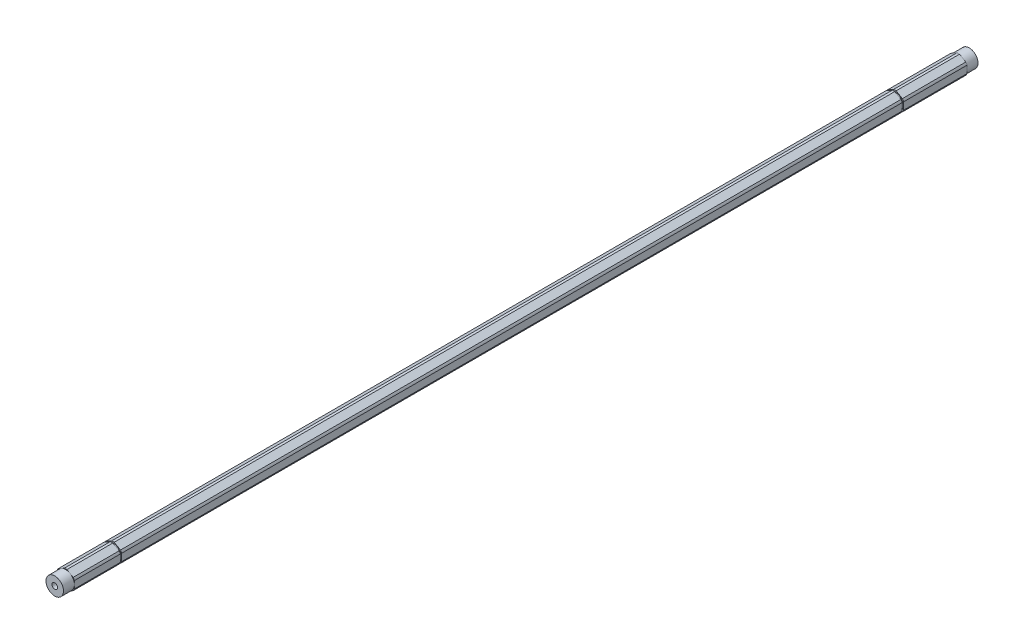
SolidWorks part; units mm, degrees
material "7075-T6 (SN)"
ref_plane "Front Plane" through (0, 0, 0) normal (0, 0, 1) x (1, 0, 0)
ref_plane "Top Plane" through (0, 0, 0) normal (0, 1, 0) x (1, 0, 0)
ref_plane "Right Plane" through (0, 0, 0) normal (1, 0, 0) x (0, 0, -1)
sketch "Sketch1" plane through (0, 0, 0) normal (0, 0, 1) x (1, 0, 0)
  line L1 (0, 7.3323) -> (-6.35, 3.6662)
  line L2 (-6.35, 3.6662) -> (-6.35, -3.6662)
  line L3 (-6.35, -3.6662) -> (0, -7.3323)
  line L4 (0, -7.3323) -> (6.35, -3.6662)
  line L5 (6.35, -3.6662) -> (6.35, 3.6662)
  line L6 (6.35, 3.6662) -> (0, 7.3323)
  circle A0 centre (0, 0) radius 6.35 construction
  circle A1 centre (0, 0) radius 2.0193
  circle A2 centre (0, 0) radius 6.875
  dimension "D1" = 12.7
  dimension "D2" = 4.0386
  dimension "D3" = 13.75
extrude "Boss-Extrude1" add sketch "Sketch1" along normal mid plane 663.575 contours L5 A2 L6 L1 L2 L3 L4 A1
sketch "Sketch2" plane through (0, 0, -331.7875) normal (0, 0, -1) x (-1, 0, 0)
  circle A0 centre (0, 0) radius 6.35
  dimension "D1" = 12.7
extrude "Cut-Extrude-Thin1" cut sketch "Sketch2" against normal blind 7.9375 thin
sketch "Sketch3" plane through (0, 0, 0) normal (0, 1, 0) x (1, 0, 0)
  line L0 (8.1546, -289.5219) -> (5.9436, -289.5219)
  line L1 (8.6172, 277.8125) -> (5.9436, 277.8125)
  line L2 (8.6172, 277.8125) -> (8.6172, 276.8219)
  line L3 (8.6172, 276.8219) -> (5.9436, 276.8219)
  line L4 (5.9436, 277.8125) -> (5.9436, 276.8219)
  line L5 (8.1546, -289.5219) -> (8.1546, -290.5125)
  line L6 (8.1546, -290.5125) -> (5.9436, -290.5125)
  line L7 (5.9436, -289.5219) -> (5.9436, -290.5125)
  line L8 (5.457, -331.7875) -> (0.893, -331.7875) construction
  line L9 (6.35, 331.7875) -> (-6.35, 331.7875) construction
  line L11 (0, -331.7875) -> (0, 323.85) construction
  dimension "D1" = 0.9906
  dimension "D2" = 53.975
  dimension "D3" = 5.9436
  dimension "D5" = 41.275
revolve "Cut-Revolve4" cut sketch "Sketch3" angle 360 about axis through (0, 0, -323.85) along (0, 0, -1)
mirror "Mirror1" about plane through (0, 0, 0) normal (0, 0, 1) of "Cut-Extrude-Thin1"
hole_wizard "#10-32 Tapped Hole1" positions "3DSketch1" profile "Sketch4" tap size "#10-32" standard "ANSI Inch"
sketch3d "3DSketch1"
  circle A0 centre (0, 0, 331.7875) radius 2.0193 construction
  circle A1 centre (0, 0, -331.7875) radius 2.0193 construction
  point P0 (0, 0, -331.7875)
  point P2 (0, 0, 331.7875)
  point P8 (0, 0, 333.8068)
  point P12 (0, 0, -329.7682)
sketch "Sketch4" plane through (0, 0, -331.7875) normal (1, 0, 0) x (0, 1, 0)
  line L0 (0, 0) -> (0, 13.2428)
  line L1 (0, 13.2428) -> (2.0193, 12.0294)
  line L2 (2.0193, 12.0294) -> (2.0193, 0)
  line L5 (2.0193, 0) -> (0, 0)
  line L10 (0, 13.2428) -> (-2.0193, 12.0294) construction
  line L11 (0, -6.35) -> (0, 107.95) construction
  dimension "Tap Drill Dia." = 4.0386
  dimension "Tap Drill Depth" = 12.0294
  dimension "Drill Angle" = 118
cosmetic thread "Hole Thread1" parameters "D1"=9.652, "D2"=4.826
cosmetic thread "Hole Thread2" parameters "D1"=9.652, "D2"=4.826
equation "\"D3@Sketch1\"=13.75mm"
